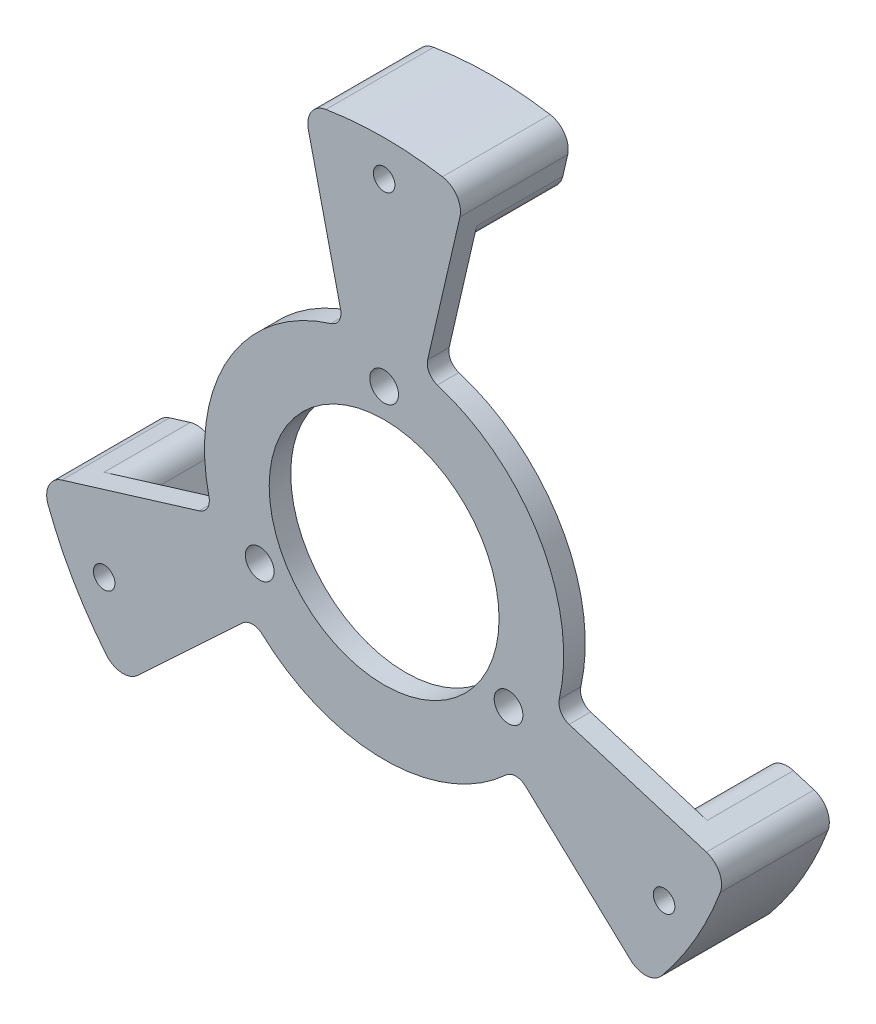
SolidWorks part; units mm, degrees
material "6061 合金"
ref_plane "前视基准面" through (0, 0, 0) normal (0, 0, 1) x (1, 0, 0)
ref_plane "上视基准面" through (0, 0, 0) normal (0, 1, 0) x (1, 0, 0)
ref_plane "右视基准面" through (0, 0, 0) normal (1, 0, 0) x (0, 0, -1)
sketch "草图1" plane through (0, 0, 0) normal (0, 0, 1) x (1, 0, 0)
  line L0 (5.6238, 24.3593) -> (11.2476, 48.7185)
  line L1 (-5.6238, 24.3593) -> (-11.2476, 48.7185)
  line L2 (0, 126.353) -> (0, -111.2679) construction
  line L3 (23.9076, -7.3093) -> (47.8152, -14.6186)
  line L4 (18.2838, -17.05) -> (36.5677, -34.0999)
  line L5 (-18.2838, -17.05) -> (-36.5677, -34.0999)
  line L6 (-23.9076, -7.3093) -> (-47.8152, -14.6186)
  arc A0 (-5.6238, 24.3593) -> (-23.9076, -7.3093) centre (0, 0) ccw
  arc A1 (11.2476, 48.7185) -> (-11.2476, 48.7185) centre (0, 0) ccw
  circle A2 centre (0, 0) radius 16
  arc A3 (36.5677, -34.0999) -> (47.8152, -14.6186) centre (0, 0) ccw
  arc A4 (-47.8152, -14.6186) -> (-36.5677, -34.0999) centre (0, 0) ccw
  arc A5 (-18.2838, -17.05) -> (18.2838, -17.05) centre (0, 0) ccw
  arc A6 (23.9076, -7.3093) -> (5.6238, 24.3593) centre (0, 0) ccw
  circle A7 centre (0, 20) radius 2
  circle A8 centre (17.3205, -10) radius 2
  circle A9 centre (-17.3205, -10) radius 2
  point P20 (0, 0)
  point P27 (0, 0)
  dimension "D1" = 26
  dimension "D3" = 100
  dimension "D4" = 50
  dimension "D5" = 32
  dimension "D7" = 20
  dimension "D8" = 4
  dimension "D2" = 13
  dimension "D6" = 3
  dimension "D9" = 3
extrude "凸台-拉伸1" add sketch "草图1" along normal blind 3
sketch "草图3" plane through (0, 0, 0) normal (0, 0, -1) x (-1, 0, 0)
  line L0 (-11.2476, 48.7185) -> (-9.223, 39.9492)
  line L1 (-5.6238, 24.3593) -> (-11.2476, 48.7185) construction
  line L2 (11.2476, 48.7185) -> (9.223, 39.9492)
  line L3 (11.2476, 48.7185) -> (5.6238, 24.3593) construction
  line L4 (47.8152, -14.6186) -> (39.2085, -11.9872)
  line L5 (36.5677, -34.0999) -> (29.9855, -27.9619)
  line L6 (-36.5677, -34.0999) -> (-29.9855, -27.9619)
  line L7 (-47.8152, -14.6186) -> (-39.2085, -11.9872)
  arc A0 (11.2476, 48.7185) -> (-11.2476, 48.7185) centre (0, 0) ccw
  arc A1 (9.223, 39.9492) -> (-9.223, 39.9492) centre (0, 0) ccw
  arc A2 (29.9855, -27.9619) -> (39.2085, -11.9872) centre (0, 0) ccw
  arc A3 (36.5677, -34.0999) -> (47.8152, -14.6186) centre (0, 0) ccw
  arc A4 (-39.2085, -11.9872) -> (-29.9855, -27.9619) centre (0, 0) ccw
  arc A5 (-47.8152, -14.6186) -> (-36.5677, -34.0999) centre (0, 0) ccw
  point P22 (0, 0)
  dimension "D1" = 41
  dimension "D2" = 3
extrude "凸台-拉伸2" add sketch "草图3" along normal blind 12
sketch "草图4" plane through (0, 0, 3) normal (0, 0, 1) x (1, 0, 0)
  circle A0 centre (0, 45) radius 1.5
  circle A1 centre (38.9711, -22.5) radius 1.5
  circle A2 centre (-38.9711, -22.5) radius 1.5
  point P9 (0, 0)
  dimension "D1" = 3
  dimension "D2" = 45
  dimension "D3" = 3
extrude "切除-拉伸1" cut sketch "草图4" against normal through all
fillet "圆角1" radius 2 6 edges at (23.9076, -7.3093, 1.5) (18.2838, -17.05, 1.5) (-18.2838, -17.05, 1.5) (-23.9076, -7.3093, 1.5) (-5.6238, 24.3593, 1.5) (5.6238, 24.3593, 1.5)
fillet "圆角2" radius 3 12 edges at (39.2085, -11.9872, -6) (47.8152, -14.6186, -4.5) (29.9855, -27.9619, -6) (36.5677, -34.0999, -4.5) (-29.9855, -27.9619, -6) (-36.5677, -34.0999, -4.5) (-47.8152, -14.6186, -4.5) (-39.2085, -11.9872, -6) (-9.223, 39.9492, -6) (-11.2476, 48.7185, -4.5) (9.223, 39.9492, -6) (11.2476, 48.7185, -4.5)
